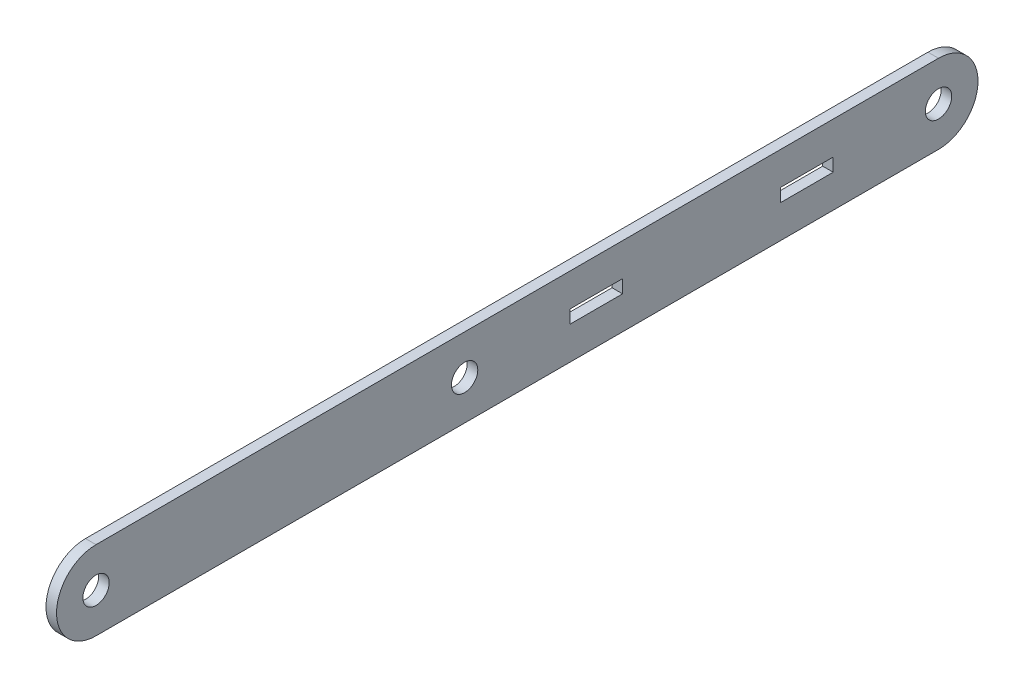
SolidWorks part; units mm, degrees
material "Lega 1060"
ref_plane "Piano frontale" through (0, 0, 0) normal (0, 0, 1) x (1, 0, 0)
ref_plane "Piano superiore" through (0, 0, 0) normal (0, 1, 0) x (1, 0, 0)
ref_plane "Piano destro" through (0, 0, 0) normal (1, 0, 0) x (0, 0, -1)
sketch "Schizzo1" plane through (0, 0, 0) normal (1, 0, 0) x (0, 0, -1)
  line L1 (80, -7.5) -> (-80, -7.5)
  line L2 (10, -1.25) -> (20, -1.25)
  line L3 (80, 7.5) -> (-80, 7.5)
  line L4 (10, -1.25) -> (10, 1.25)
  line L5 (80, -7.5) -> (-80, 7.5) construction
  line L6 (80, 7.5) -> (-80, -7.5) construction
  line L7 (10, 1.25) -> (20, 1.25)
  line L8 (20, -1.25) -> (20, 1.25)
  line L9 (60, 1.25) -> (50, 1.25)
  line L10 (60, 1.25) -> (60, -1.25)
  line L11 (60, -1.25) -> (50, -1.25)
  line L12 (50, 1.25) -> (50, -1.25)
  arc A0 (-80, 7.5) -> (-80, -7.5) centre (-80, 0) ccw
  arc A1 (80, 7.5) -> (80, -7.5) centre (80, 0) cw
  circle A2 centre (-80, 0) radius 2.5
  circle A3 centre (80, 0) radius 2.5
  circle A4 centre (-10, 0) radius 2.5
  point P0 (0, 0)
  dimension "D2" = 5
  dimension "D3" = 160
  dimension "D4" = 70
  dimension "D1" = 15
extrude "Estrusione-Estrusione1" add sketch "Schizzo1" along normal blind 2
